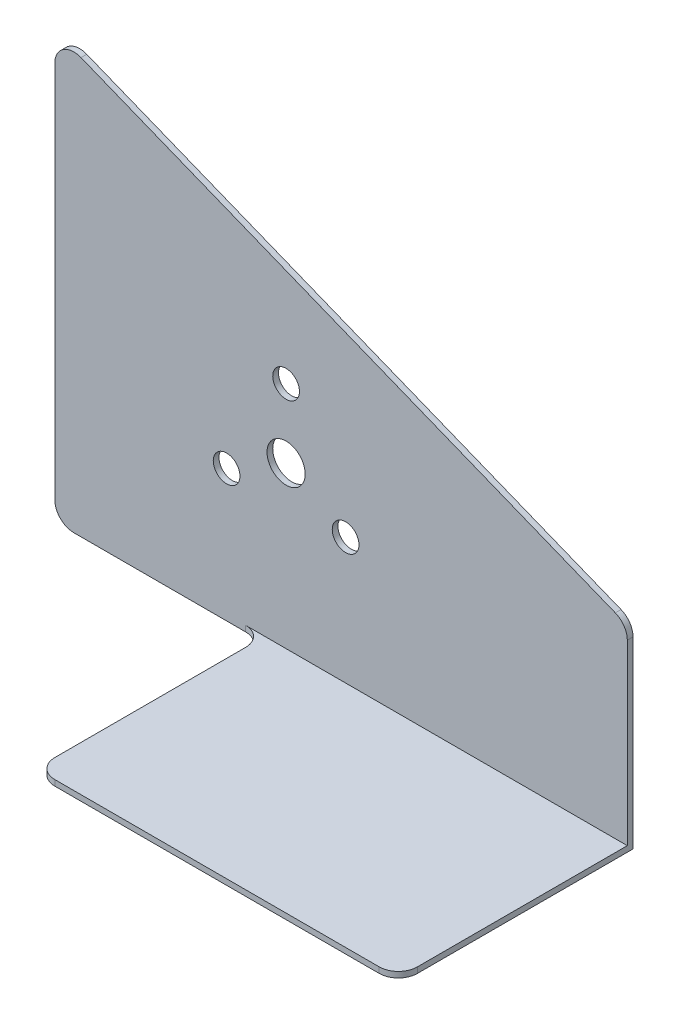
SolidWorks part; units mm, degrees
ref_plane "Front Plane" through (0, 0, 0) normal (0, 0, 1) x (1, 0, 0)
ref_plane "Top Plane" through (0, 0, 0) normal (0, 1, 0) x (1, 0, 0)
ref_plane "Right Plane" through (0, 0, 0) normal (1, 0, 0) x (0, 0, -1)
sketch "Sketch1" plane through (0, 0, 0) normal (0, 0, 1) x (1, 0, 0)
  line L0 (0, 0) -> (190, 0)
  dimension "D1" = 190
extrude "Extrude-Thin1" add sketch "Sketch1" along normal blind 120 thin
sketch "Sketch3" plane through (0, 0, 0) normal (0, 0, -1) x (-1, 0, 0)
  line L0 (-190, 0) -> (-190, 100)
  line L1 (-190, 100) -> (110, 220)
  line L2 (110, 220) -> (110, 0)
  line L3 (-190, 0) -> (-190, -3)
  line L4 (-190, -3) -> (110, -3)
  line L5 (110, -3) -> (110, 0)
  dimension "D1" = 300
  dimension "D2" = 100
  dimension "D3" = 220
extrude "Boss-Extrude1" add sketch "Sketch3" along normal blind 3
fillet "Fillet2" radius 10 6 edges at (-110, -3, -1.5) (-110, 220, -1.5) (190, 100, -1.5) (190, -1.5, 120) (0, -1.5, 120) (0, -1.5, 0)
sketch "Sketch4" plane through (0, 0, -3) normal (0, 0, -1) x (-1, 0, 0)
  circle A0 centre (-42.3722, 66.2) radius 7
  circle A1 centre (19.9816, 66.2) radius 7
  circle A2 centre (-11.1953, 120.2) radius 7
  circle A3 centre (-11.1953, 84.2) radius 10
extrude "Cut-Extrude1" cut sketch "Sketch4" against normal blind 3
